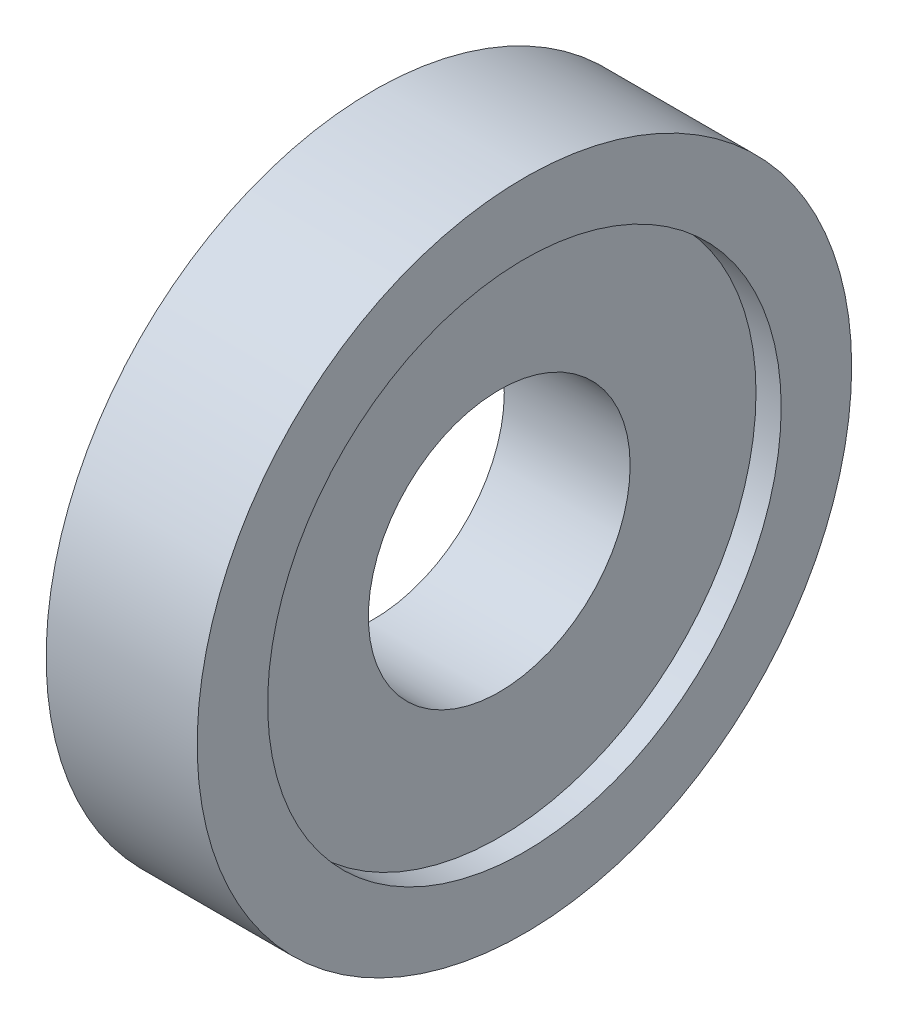
SolidWorks part; units mm, degrees
material "POM 乙缩醛共聚物"
ref_plane "前视基准面" through (0, 0, 0) normal (0, 0, 1) x (1, 0, 0)
ref_plane "上视基准面" through (0, 0, 0) normal (0, 1, 0) x (1, 0, 0)
ref_plane "右视基准面" through (0, 0, 0) normal (1, 0, 0) x (0, 0, -1)
other "Configuration Table"
sketch "草图1" plane through (0, 0, 0) normal (0, 0, 1) x (1, 0, 0)
  line L0 (3.746, 0) -> (0, 0) construction
  line L1 (0, 0) -> (0, 2.6) construction
  line L2 (0, 2.6) -> (0, 6.5)
  line L3 (0, 6.5) -> (3, 6.5)
  line L4 (3, 6.5) -> (3, 5.1)
  line L5 (3, 5.1) -> (2.5, 5.1)
  line L6 (2.5, 5.1) -> (2.5, 2.6)
  line L7 (2.5, 2.6) -> (0, 2.6)
  dimension "D1" = 13
  dimension "D2" = 3
  dimension "D3" = 0.5
  dimension "D4" = 5.2
  dimension "D5" = 10.2
revolve "旋转1" add sketch "草图1" angle 360 about L0
